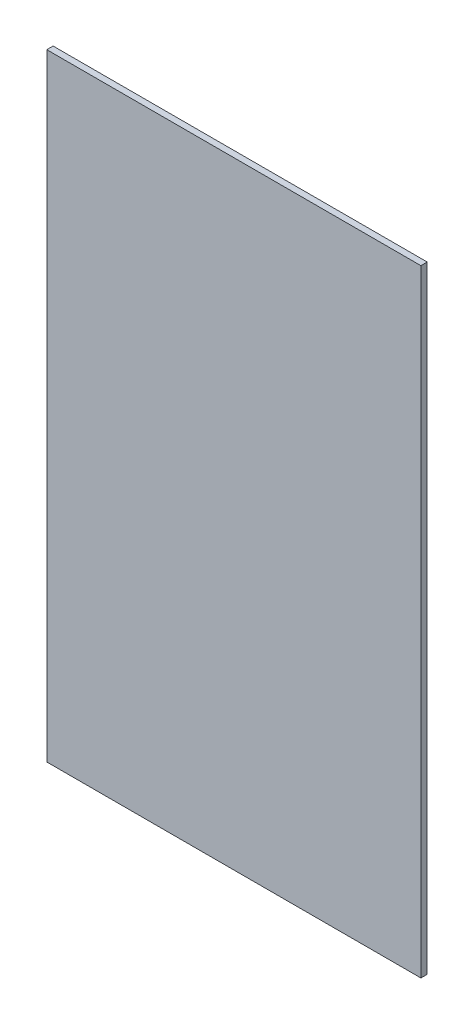
SolidWorks part; units mm, degrees
ref_plane "Front Plane" through (0, 0, 0) normal (0, 0, 1) x (1, 0, 0)
ref_plane "Top Plane" through (0, 0, 0) normal (0, 1, 0) x (1, 0, 0)
ref_plane "Right Plane" through (0, 0, 0) normal (1, 0, 0) x (0, 0, -1)
sketch "Sketch1" plane through (0, 0, 0) normal (0, 0, 1) x (1, 0, 0)
  line L1 (-88.5825, 146.05) -> (88.5825, 146.05)
  line L2 (-88.5825, 146.05) -> (-88.5825, -146.05)
  line L3 (-88.5825, -146.05) -> (88.5825, -146.05)
  line L4 (88.5825, 146.05) -> (88.5825, -146.05)
  line L5 (-88.5825, 146.05) -> (88.5825, -146.05) construction
  line L6 (-88.5825, -146.05) -> (88.5825, 146.05) construction
  point P0 (0, 0)
  dimension "D1" = 177.165
  dimension "D2" = 292.1
extrude "Boss-Extrude1" add sketch "Sketch1" along normal blind 2.9972
